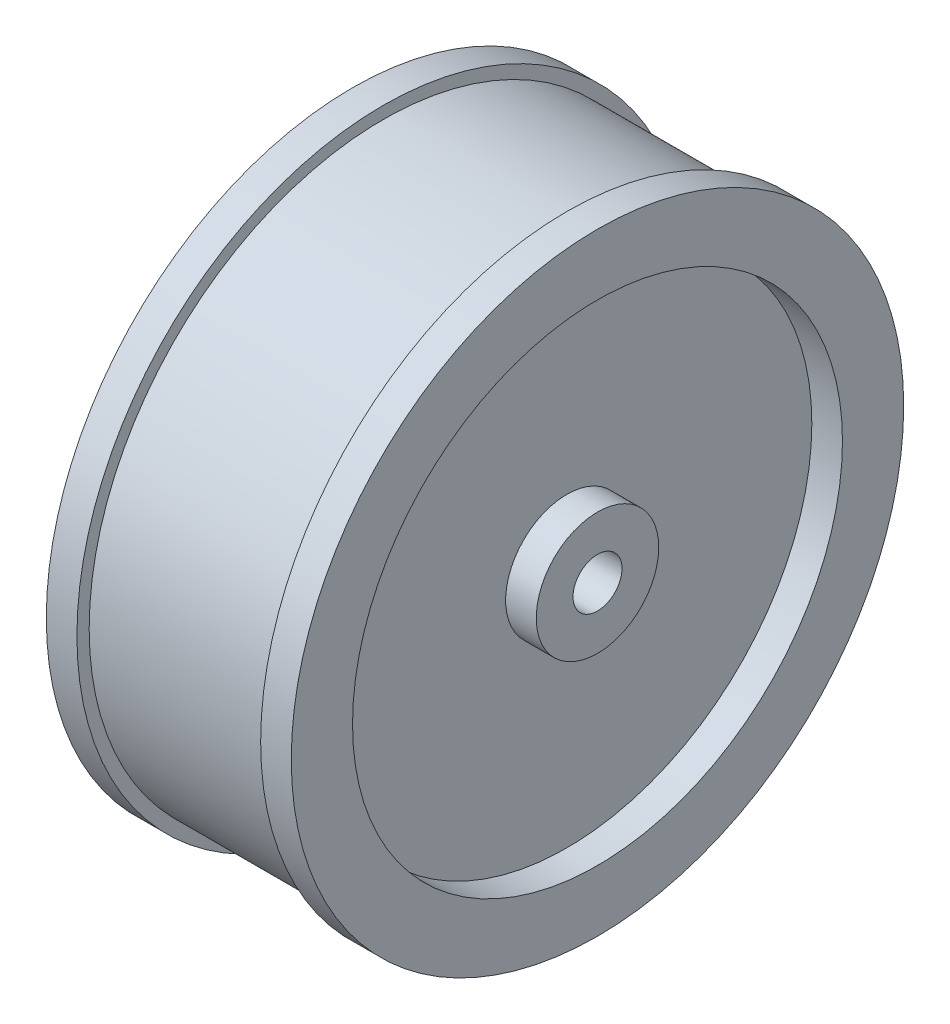
SolidWorks part; units mm, degrees
other "Markup1"
sketch "Sketch9" plane through (0, 47, -47) normal (0.9015, 0.3997, -0.1662) x (-0.0997, -0.1821, -0.9782)
other "Markup2"
sketch "Sketch10" plane through (0, -47, -47) normal (0.9887, -0.0139, -0.1494) x (0.0269, -0.9631, 0.2679)
material "Nylon 101"
ref_plane "Front Plane" through (0, 0, 0) normal (0, 0, 1) x (1, 0, 0)
ref_plane "Top Plane" through (0, 0, 0) normal (0, 1, 0) x (1, 0, 0)
ref_plane "Right Plane" through (0, 0, 0) normal (1, 0, 0) x (0, 0, -1)
sketch "Sketch1" plane through (0, 0, 0) normal (0, 0, 1) x (1, 0, 0)
  line L0 (0, 0) -> (-43.1356, 0) construction
  line L1 (0, 4) -> (-40, 4)
  line L2 (-40, 4) -> (-40, 10)
  line L3 (-40, 10) -> (-35, 10)
  line L4 (-35, 10) -> (-35, 40)
  line L5 (-35, 40) -> (-40, 40)
  line L6 (-40, 40) -> (-40, 48)
  line L7 (-35, 48) -> (-5, 48)
  line L9 (0, 40) -> (-5, 40)
  line L10 (-5, 40) -> (-5, 10)
  line L11 (-5, 10) -> (0, 10)
  line L12 (0, 10) -> (0, 4)
  line L15 (0, 40) -> (0, 50)
  line L16 (0, 50) -> (-5, 50)
  line L17 (-5, 48) -> (-5, 50)
  line L19 (-40, 48) -> (-40, 50)
  line L20 (-40, 50) -> (-35, 50)
  line L21 (-35, 48) -> (-35, 50)
  dimension "D1" = 4
  dimension "D2" = 30
  dimension "D3" = 40
  dimension "D4" = 30
  dimension "D5" = 6
  dimension "D6" = 10
  dimension "D7" = 5
  dimension "D8" = 5
  dimension "D9" = 10
  dimension "D10" = 2
  dimension "D11" = 5
revolve "Revolve1" add sketch "Sketch1" angle 360 about L0
